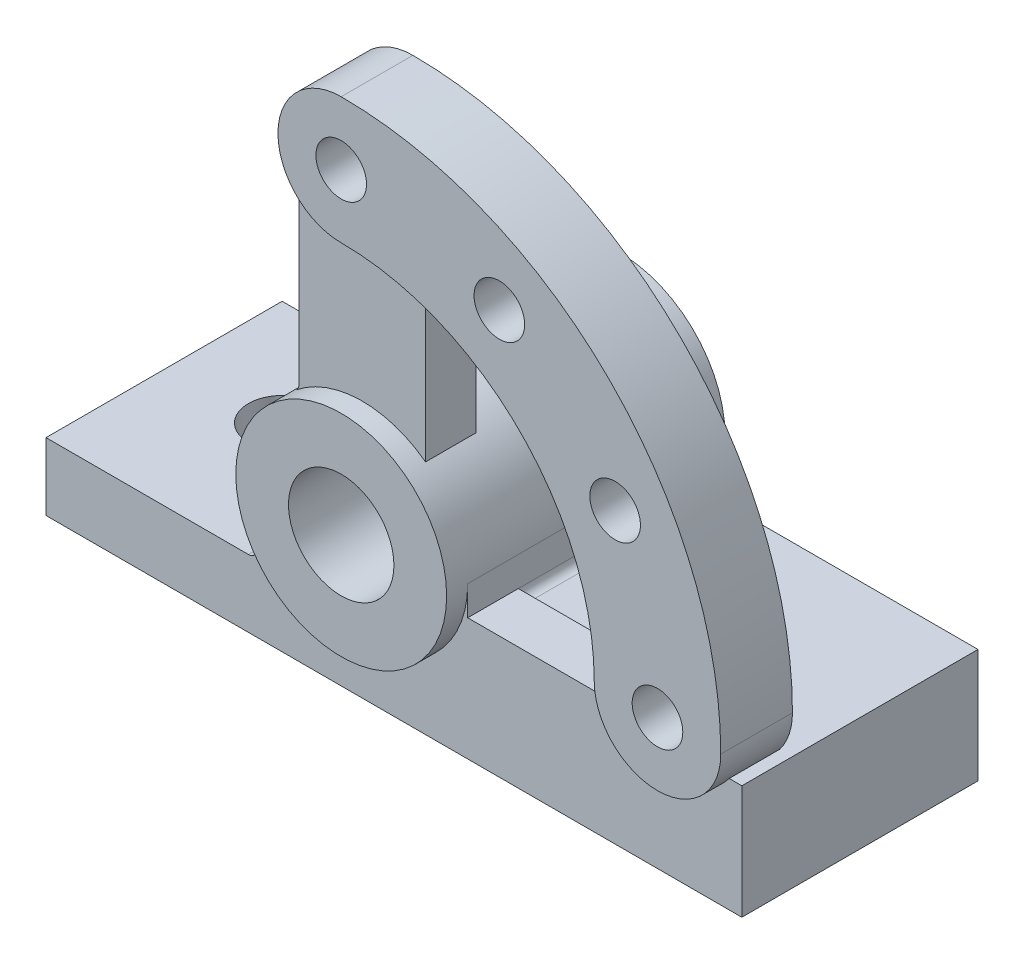
SolidWorks part; units mm, degrees
material "6061-T4 (SS)"
ref_plane "Front Plane" through (0, 0, 0) normal (0, 0, 1) x (1, 0, 0)
ref_plane "Top Plane" through (0, 0, 0) normal (0, 1, 0) x (1, 0, 0)
ref_plane "Right Plane" through (0, 0, 0) normal (1, 0, 0) x (0, 0, -1)
sketch "Sketch10" plane through (0, 0, 0) normal (0, 0, 1) x (1, 0, 0)
  line L0 (0, 89.1197) -> (0, -73.9862) construction
  line L1 (-126.5332, 0) -> (122.3294, 0) construction
  circle A0 centre (0, 0) radius 12.5
  circle A1 centre (0, 0) radius 25
  dimension "D1" = 25
  dimension "D2" = 50
extrude "Boss-Extrude7" add sketch "Sketch10" along normal mid plane 66
sketch "Sketch12" plane through (0, 0, 33) normal (0, 0, -1) x (-1, 0, 0)
  line L0 (0, 0) -> (0, -36) construction
  line L1 (0, -36) -> (75, -36)
  line L2 (75, -36) -> (75, -20)
  line L3 (25, 0) -> (25, -18)
  line L4 (27, -20) -> (75, -20)
  line L5 (0, -36) -> (-90, -36)
  line L6 (-90, -36) -> (-90, -9)
  line L7 (-25, 0) -> (-25, -7)
  line L8 (-27, -9) -> (-90, -9)
  circle A0 centre (0, 0) radius 25 construction
  arc A1 (25, 0) -> (-25, 0) centre (0, 0) cw
  arc A2 (-25, -7) -> (-27, -9) centre (-27, -7) cw
  arc A3 (25, -18) -> (27, -20) centre (27, -18) ccw
  dimension "D7" = 2
  dimension "D1" = 50
  dimension "D2" = 75
  dimension "D3" = 90
  dimension "D4" = 16
  dimension "D5" = 27
  dimension "D6" = 36
extrude "Boss-Extrude9" add sketch "Sketch12" along normal blind 56 from offset 5 separate body
sketch "Sketch13" plane through (0, -20, 0) normal (0, 1, 0) x (1, 0, 0)
  line L1 (-75, 28) -> (-27, 28) construction
  line L3 (-75, 28) -> (-75, -28) construction
  circle A0 centre (-50, 3) radius 8
  dimension "D1" = 16
  dimension "D3" = 25
  dimension "D2" = 25
extrude "Cut-Extrude1" cut sketch "Sketch13" against normal blind 16 contours A0
sketch "Sketch15" plane through (0, 0, 33) normal (0, 0, 1) x (1, 0, 0)
  line L0 (0, 0) -> (0, 75) construction
  line L1 (0, 0) -> (75, 0) construction
  line L2 (0, 0) -> (49.0645, 84.9822) construction
  line L3 (0, 0) -> (92.3239, 53.3032) construction
  arc A0 (60, 0) -> (0, 60) centre (0, 0) ccw
  arc A1 (90, 0) -> (0, 90) centre (0, 0) ccw
  arc A3 (0, 90) -> (0, 60) centre (0, 75) ccw
  arc A4 (60, 0) -> (90, 0) centre (75, 0) ccw
  circle A5 centre (0, 75) radius 6
  circle A6 centre (75, 0) radius 6
  circle A7 centre (37.5, 64.9519) radius 6
  circle A8 centre (64.9519, 37.5) radius 6
  dimension "D1" = 30
  dimension "D3" = 12
  dimension "D4" = 12
  dimension "D5" = 12
  dimension "D6" = 12
  dimension "D8" = 15
  dimension "D10" = 90
  dimension "D2" = 30
  dimension "D7" = 60
  dimension "D9" = 15
extrude "Boss-Extrude12" add sketch "Sketch15" against normal blind 17 separate body contours A0 A4 A1 A3 A8 A7 A6 A5
sketch "Sketch17" plane through (0, 0, 33) normal (0, 0, 1) x (1, 0, 0)
  line L0 (0, 0) -> (0, 75) construction
  line L1 (0, 0) -> (75, 0) construction
  line L2 (0, 0) -> (37.5, 64.9519) construction
  line L3 (0, 0) -> (64.9519, 37.5) construction
  circle A3 centre (0, 75) radius 6
  circle A4 centre (37.5, 64.9519) radius 6
  circle A5 centre (64.9519, 37.5) radius 6
  circle A6 centre (75, 0) radius 6
  point P12 (-25.2563, 121.3263)
  point P16 (-33.5572, 121.3263)
  dimension "D1" = 30
  dimension "D3" = 12
  dimension "D5" = 12
  dimension "D6" = 12
  dimension "D7" = 12
  dimension "D2" = 30
  dimension "D4" = 75
  dimension "D8" = 75
  dimension "D9" = 75
  dimension "D10" = 75
extrude "Cut-Extrude2" cut sketch "Sketch17" against normal blind 17 contours A3 | A4 | A5 | A6
sketch "Sketch18" plane through (0, 0, 28) normal (0, 0, 1) x (1, 0, 0)
  line L0 (0, 0) -> (0, 75) construction
  line L1 (25, -7) -> (58, -7)
  line L2 (60, -5) -> (60, 0)
  line L3 (-15, 75) -> (-15, 20)
  line L4 (15, 58.0948) -> (15, 20)
  line L8 (27, -9) -> (63, -9)
  line L9 (27, -9) -> (90, -9) construction
  arc A0 (0, 90) -> (0, 60) centre (0, 75) ccw construction
  circle A1 centre (0, 0) radius 25 construction
  arc A2 (-15, 75) -> (0, 60) centre (0, 75) ccw
  arc A4 (58, -7) -> (60, -5) centre (58, -5) ccw
  arc A5 (15, 20) -> (-15, 20) centre (0, 0) ccw
  arc A6 (15, 58.0948) -> (0, 60) centre (0, 0) ccw
  arc A7 (60, 0) -> (63, -9) centre (75, 0) ccw
  arc A8 (25, -7) -> (27, -9) centre (27, -7) ccw
  dimension "D2" = 2
  dimension "D1" = 30
extrude "Boss-Extrude13" add sketch "Sketch18" against normal blind 12
sketch "Sketch20" plane through (0, -9, 0) normal (0, 1, 0) x (1, 0, 0)
  line L0 (-50, 3) -> (95.5489, 3) construction
  line L1 (0, -61.7866) -> (0, 61.2299) construction
  circle A0 centre (57.5, 3) radius 8
  dimension "D1" = 16
  dimension "D2" = 57.5
extrude "Cut-Extrude3" cut sketch "Sketch20" against normal blind 27 contours A0
fillet "Fillet1" radius 2 1 edges at (-15, 20, 22)
